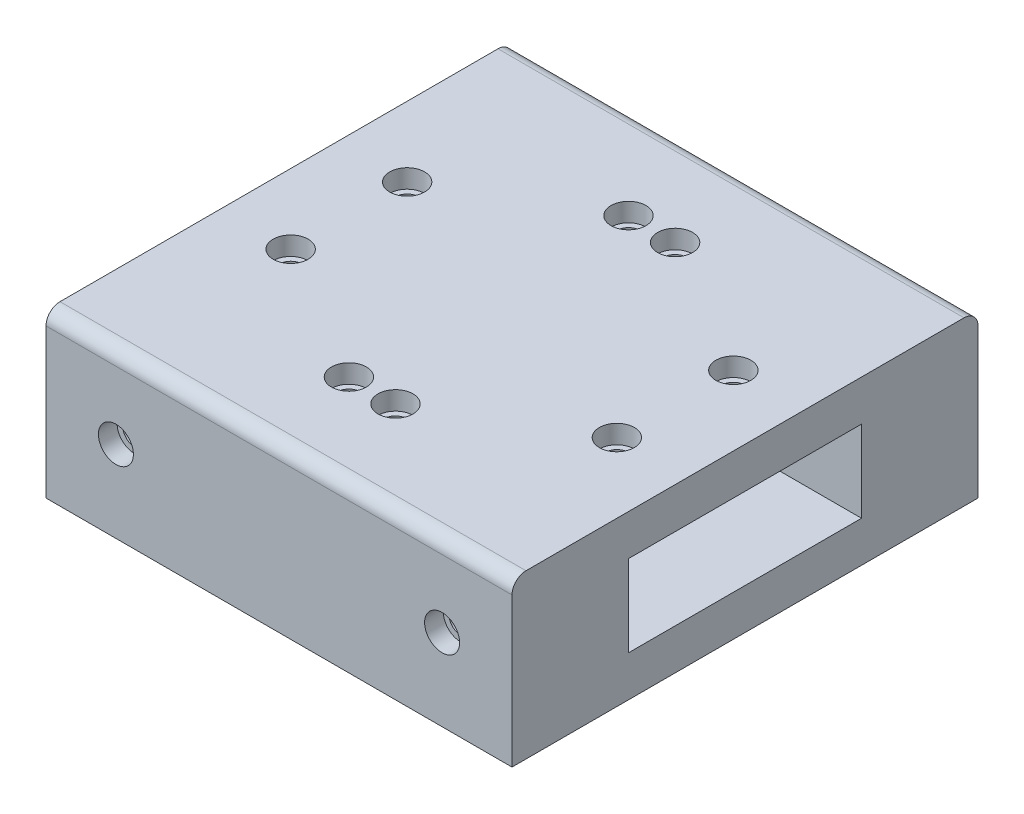
SolidWorks part; units mm, degrees
ref_plane "Front Plane" through (0, 0, 0) normal (0, 0, 1) x (1, 0, 0)
ref_plane "Top Plane" through (0, 0, 0) normal (0, 1, 0) x (1, 0, 0)
ref_plane "Right Plane" through (0, 0, 0) normal (1, 0, 0) x (0, 0, -1)
sketch "Sketch1" plane through (0, 0, 0) normal (0, 1, 0) x (1, 0, 0)
  line L0 (0, 0) -> (-63894.7551, 0) construction
  line L1 (0, 0) -> (0, -63894.7551) construction
  line L3 (-50, 50) -> (50, 50)
  line L4 (-50, 50) -> (-50, -50)
  line L5 (-50, -50) -> (50, -50)
  line L6 (50, 50) -> (50, -50)
  line L7 (-50, 50) -> (50, -50) construction
  line L8 (-50, -50) -> (50, 50) construction
  point P5 (0, 0)
  dimension "D1" = 100
extrude "Boss-Extrude1" add sketch "Sketch1" along normal blind 35
sketch "Sketch2" plane through (50, 0, 0) normal (1, 0, 0) x (0, 0, -1)
  line L0 (0, 0) -> (0, -50000) construction
  line L1 (-50, 0) -> (50, 0) construction
  line L2 (-50, 17.5) -> (49950, 17.5) construction
  line L3 (-50, 35) -> (-50, 0) construction
  line L5 (-25, 26.25) -> (25, 26.25)
  line L6 (-25, 26.25) -> (-25, 8.75)
  line L7 (-25, 8.75) -> (25, 8.75)
  line L8 (25, 26.25) -> (25, 8.75)
  line L9 (-25, 26.25) -> (25, 8.75) construction
  line L10 (-25, 8.75) -> (25, 26.25) construction
  point P4 (0, 0)
  point P9 (-50, 17.5)
  point P10 (0, 17.5)
  dimension "D1" = 50
  dimension "D2" = 17.5
extrude "Cut-Extrude1" cut sketch "Sketch2" against normal blind 30
mirror "Mirror1" about plane through (0, 0, 0) normal (1, 0, 0) of "Cut-Extrude1"
sketch "Sketch3" plane through (0, 35, 0) normal (0, 1, 0) x (1, 0, 0)
  line L0 (0, 0) -> (-50000, 0) construction
  line L1 (0, 0) -> (0, -50000) construction
  line L2 (35, 50) -> (35, -49950) construction
  line L4 (50, -50) -> (50, 50) construction
  circle A0 centre (35, 12.5) radius 2.5
  circle A1 centre (35, -12.5) radius 2.5
  circle A2 centre (-35, -12.5) radius 2.5
  circle A3 centre (-35, 12.5) radius 2.5
  dimension "D2" = 5
  dimension "D3" = 12.5
  dimension "D1" = 15
extrude "Cut-Extrude2" cut sketch "Sketch3" against normal blind 10
sketch "Sketch4" plane through (0, 35, 0) normal (0, 1, 0) x (1, 0, 0)
  line L0 (0, 0) -> (-50000, 0) construction
  line L1 (0, 0) -> (0, -50000) construction
  circle A0 centre (35, 12.5) radius 3.75
  circle A1 centre (35, -12.5) radius 3.75
  circle A2 centre (-35, -12.5) radius 3.75
  circle A3 centre (-35, 12.5) radius 3.75
  dimension "D1" = 7.5
extrude "Cut-Extrude3" cut sketch "Sketch4" against normal blind 4
sketch "Sketch5" plane through (0, 0, -50) normal (0, 0, -1) x (-1, 0, 0)
  line L0 (0, 0) -> (0, -50000) construction
  line L1 (-50, 0) -> (50, 0) construction
  line L3 (-50, 17.5) -> (49950, 17.5) construction
  line L4 (-50, 35) -> (-50, 0) construction
  line L5 (-35, 35) -> (-35, -49965) construction
  circle A0 centre (-35, 17.5) radius 2.5
  circle A1 centre (35, 17.5) radius 2.5
  point P4 (0, 0)
  point P11 (-50, 17.5)
  dimension "D2" = 5
  dimension "D1" = 15
extrude "Cut-Extrude4" cut sketch "Sketch5" against normal blind 30
sketch "Sketch6" plane through (0, 0, -50) normal (0, 0, -1) x (-1, 0, 0)
  line L0 (0, 0) -> (0, -50000) construction
  circle A0 centre (-35, 17.5) radius 3.75
  circle A1 centre (35, 17.5) radius 3.75
  dimension "D1" = 7.5
extrude "Cut-Extrude5" cut sketch "Sketch6" against normal blind 4
mirror "Mirror2" about plane through (0, 0, 0) normal (0, 0, 1) of "Cut-Extrude5", "Cut-Extrude4"
sketch "Sketch7" plane through (0, 35, 0) normal (0, 1, 0) x (1, 0, 0)
  line L0 (0, 0) -> (-50000, 0) construction
  line L1 (0, 0) -> (0, -50000) construction
  line L2 (50, 50) -> (-50, 50) construction
  line L3 (50, -50) -> (50, 50) construction
  circle A0 centre (5, 30) radius 2.5
  circle A1 centre (5, -30) radius 2.5
  circle A2 centre (-5, -30) radius 2.5
  circle A3 centre (-5, 30) radius 2.5
  dimension "D1" = 5
  dimension "D2" = 20
  dimension "D3" = 45
extrude "Cut-Extrude10" cut sketch "Sketch7" against normal through all
sketch "Sketch8" plane through (0, 35, 0) normal (0, 1, 0) x (1, 0, 0)
  line L0 (0, 0) -> (-50000, 0) construction
  line L1 (0, 0) -> (0, -50000) construction
  circle A0 centre (-5, 30) radius 3.75
  circle A1 centre (5, 30) radius 3.75
  circle A2 centre (5, -30) radius 3.75
  circle A3 centre (-5, -30) radius 3.75
  dimension "D1" = 7.5
extrude "Cut-Extrude11" cut sketch "Sketch8" against normal blind 4
fillet "Fillet1" radius 3 2 edges at (0, 35, 50) (0, 35, -50)
